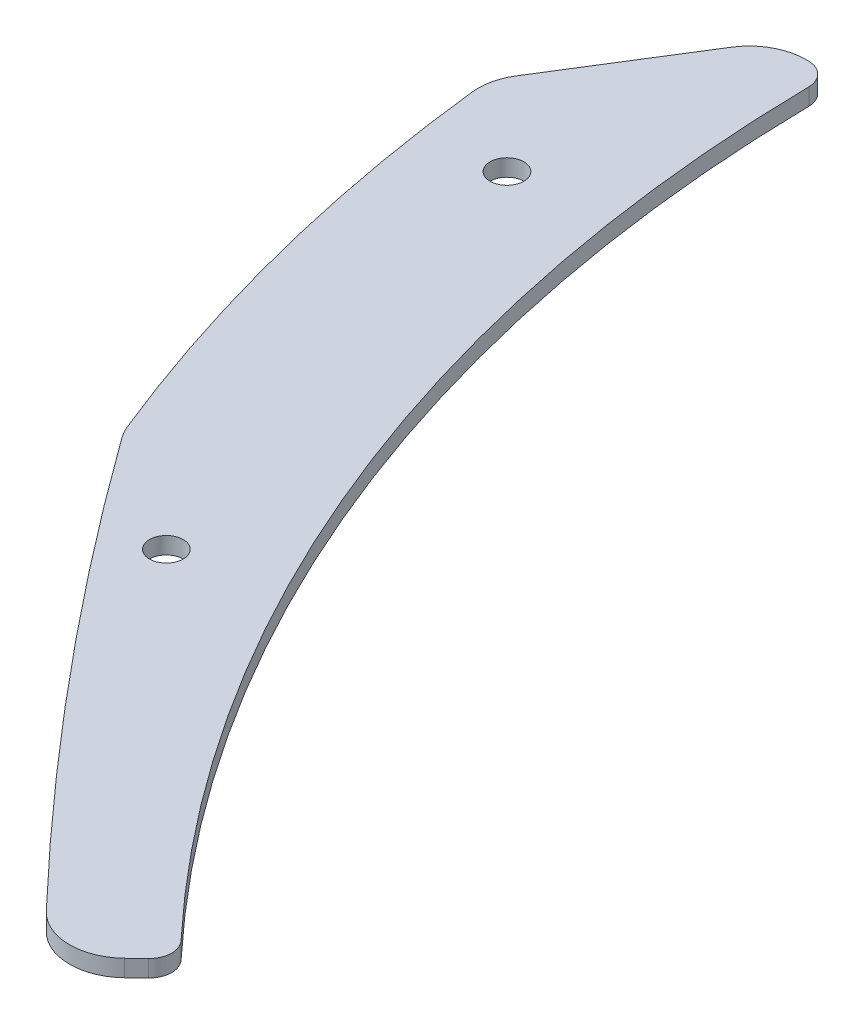
SolidWorks part; units mm, degrees
material "ABS"
ref_plane "Plan de face" through (0, 0, 0) normal (0, 0, 1) x (1, 0, 0)
ref_plane "Plan de dessus" through (0, 0, 0) normal (0, 1, 0) x (1, 0, 0)
ref_plane "Plan de droite" through (0, 0, 0) normal (1, 0, 0) x (0, 0, -1)
sketch "Esquisse1" plane through (0, 0, 0) normal (0, 1, 0) x (1, 0, 0)
  line L0 (-155, 0) -> (-139.5, 0)
  line L1 (-100.3479, -96.9048) -> (-111.4977, -107.672)
  line L2 (-146.3743, -21.8758) -> (0, 0) construction
  line L3 (0, 0) -> (-132.4503, -66.0373) construction
  arc A0 (-155, 0) -> (-111.4977, -107.672) centre (0, 0) ccw
  arc A1 (-148, 0) -> (-106.4623, -102.8094) centre (0, 0) ccw construction
  arc A2 (-139.5, 0) -> (-100.3479, -96.9048) centre (0, 0) ccw
  circle A3 centre (-146.3743, -21.8758) radius 1.5
  circle A4 centre (-132.4503, -66.0373) radius 1.5
  dimension "D1" = 139.5
  dimension "D2" = 148
  dimension "D3" = 155
  dimension "D4" = 3
  dimension "D8" = 46.3046
  dimension "D5" = 8.5
  dimension "D6" = 18
  dimension "D7" = 17.5
extrude "Boss.-Extru.1" add sketch "Esquisse1" along normal blind 1.5
sketch "Esquisse2" plane through (0, 1.5, 0) normal (0, 1, 0) x (1, 0, 0)
  line L0 (-155, 0) -> (-144.5, 0)
  line L1 (-111.4977, -107.672) -> (-100.3479, -96.9048) construction
  line L2 (-106.4615, -102.8087) -> (-111.4977, -107.672)
  line L3 (-139.5, 0) -> (-155, 0) construction
  line L4 (-144.5, 0) -> (-154.2174, -15.5562)
  circle A0 centre (-146.3743, -21.8758) radius 1.5 construction
  arc A1 (-143.363, -58.9241) -> (-106.4615, -102.8087) centre (165.1013, 162.9989) ccw
  arc A2 (-155, 0) -> (-111.4977, -107.672) centre (0, 0) ccw construction
  arc A3 (-155, 0) -> (-154.2174, -15.5562) centre (0, 0) ccw
  arc A4 (-143.363, -58.9241) -> (-111.4977, -107.672) centre (0, 0) ccw
  arc A6 (-166.5613, -22.4733) -> (-111.7637, -97.2813) centre (165.1013, 162.9989) ccw construction
  dimension "D1" = 5
  dimension "D2" = 10
extrude "Enlèv. mat.-Extru.1" cut sketch "Esquisse2" against normal through all
fillet "Congé1" radius 5 4 edges at (-144.5, 0.75, 0) (-154.2174, 0.75, 15.5562) (-143.363, 0.75, 58.9241) (-106.4615, 0.75, 102.8087)
fillet "Congé2" radius 2 2 edges at (-139.5, 0.75, 0) (-100.3479, 0.75, 96.9048)
